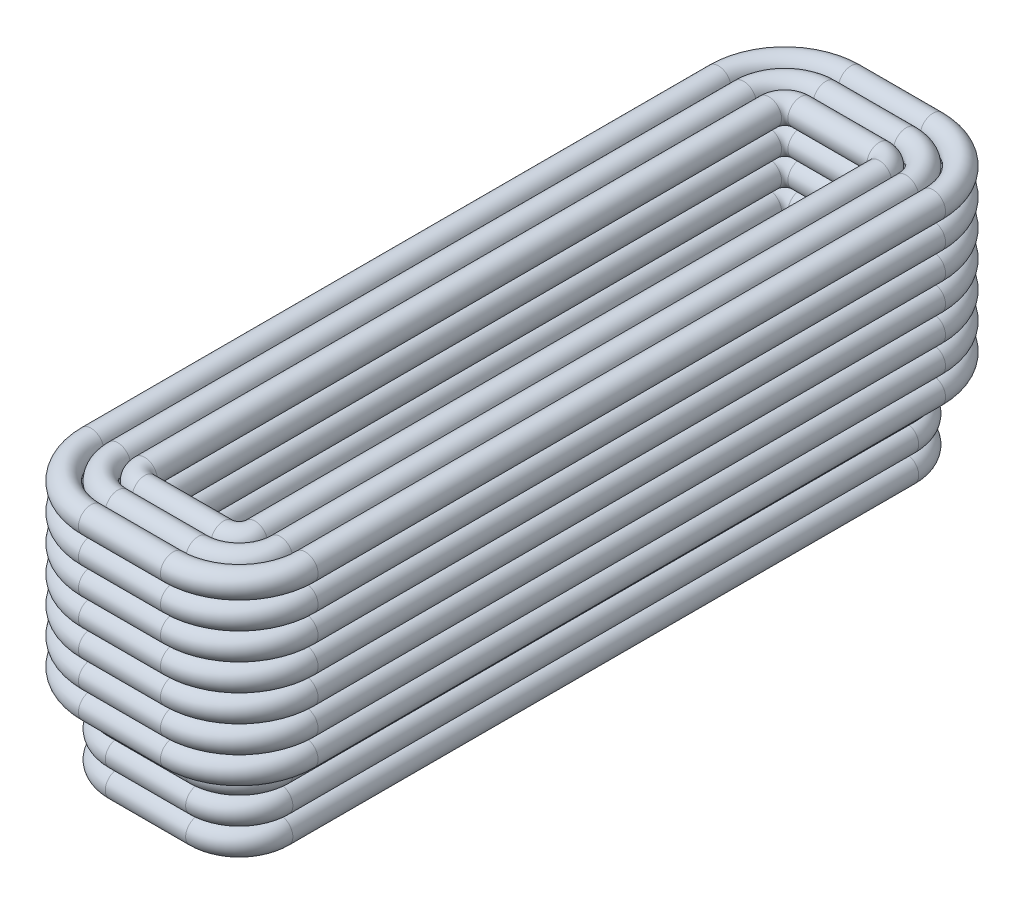
SolidWorks part; units mm, degrees
material "Copper"
ref_plane "Front Plane" through (0, 0, 0) normal (0, 0, 1) x (1, 0, 0)
ref_plane "Top Plane" through (0, 0, 0) normal (0, 1, 0) x (1, 0, 0)
ref_plane "Right Plane" through (0, 0, 0) normal (1, 0, 0) x (0, 0, -1)
ref_plane "Plane1" through (0, 41.1208, 0) normal (0, 1, 0) x (1, 0, 0)
sketch "Sketch2" plane through (0, 41.1208, 0) normal (0, 1, 0) x (1, 0, 0)
  line L1 (-1.25, -20.4) -> (1.25, -20.4)
  line L2 (-1.75, -19.9) -> (-1.75, -0.1)
  line L3 (-1.25, 0.4) -> (1.25, 0.4)
  line L4 (1.75, -19.9) -> (1.75, -0.1)
  line L5 (-1.75, -20.4) -> (1.75, 0.4) construction
  line L6 (-1.75, 0.4) -> (1.75, -20.4) construction
  line L7 (0, 0) -> (0, -10) construction
  arc A0 (-1.75, -0.1) -> (-1.25, 0.4) centre (-1.25, -0.1) cw
  arc A1 (1.25, 0.4) -> (1.75, -0.1) centre (1.25, -0.1) cw
  arc A2 (1.25, -20.4) -> (1.75, -19.9) centre (1.25, -19.9) ccw
  arc A3 (-1.25, -20.4) -> (-1.75, -19.9) centre (-1.25, -19.9) cw
  point P0 (0, -10)
  point P5 (0, -10)
  dimension "D4" = 0.5
  dimension "D1" = 10
  dimension "D2" = 20.8
  dimension "D3" = 3.5
sweep "Sweep1" add path "Sketch2" circular profile diameter 0.8 parameters "D3"=0.8
sketch "Sketch4" plane through (0, 41.1208, 0) normal (0, 1, 0) x (1, 0, 0)
  line L1 (-1.275, 1.225) -> (1.275, 1.225)
  line L2 (-2.575, -0.075) -> (-2.575, -19.925)
  line L3 (-1.275, -21.225) -> (1.275, -21.225)
  line L4 (2.575, -0.075) -> (2.575, -19.925)
  line L5 (-2.575, 1.225) -> (2.575, -21.225) construction
  line L6 (-2.575, -21.225) -> (2.575, 1.225) construction
  arc A0 (1.275, 1.225) -> (2.575, -0.075) centre (1.275, -0.075) cw
  arc A1 (-1.275, 1.225) -> (-2.575, -0.075) centre (-1.275, -0.075) ccw
  arc A2 (1.275, -21.225) -> (2.575, -19.925) centre (1.275, -19.925) ccw
  arc A3 (-2.575, -19.925) -> (-1.275, -21.225) centre (-1.275, -19.925) ccw
  point P0 (0, -10)
  point P6 (0, -10)
  dimension "D3" = 1.3
  dimension "D1" = 22.45
  dimension "D2" = 5.15
sweep "Sweep2" add path "Sketch4" circular profile diameter 0.8 parameters "D3"=0.8
pattern_linear "LPattern1" count 10 spacing 0.85 along (0, 1, 0) of "Sweep1"
ref_plane "Plane2" through (0, 48.7708, 0) normal (0, 1, 0) x (1, 0, 0)
sketch "Sketch351" plane through (0, 48.7708, 0) normal (0, 1, 0) x (1, 0, 0)
  line L1 (-1.3, -22.05) -> (1.3, -22.05)
  line L2 (-3.4, -19.95) -> (-3.4, -0.05)
  line L3 (-1.3, 2.05) -> (1.3, 2.05)
  line L4 (3.4, -19.95) -> (3.4, -0.05)
  line L5 (-3.4, -22.05) -> (3.4, 2.05) construction
  line L6 (-3.4, 2.05) -> (3.4, -22.05) construction
  arc A0 (1.3, -22.05) -> (3.4, -19.95) centre (1.3, -19.95) ccw
  arc A1 (-1.3, -22.05) -> (-3.4, -19.95) centre (-1.3, -19.95) cw
  arc A2 (-3.4, -0.05) -> (-1.3, 2.05) centre (-1.3, -0.05) cw
  arc A3 (1.3, 2.05) -> (3.4, -0.05) centre (1.3, -0.05) cw
  point P0 (0, -10)
  point P18 (0, 0)
  point P19 (0, 0)
  point P20 (1.2, -19.85)
  point P21 (1.2, -19.85)
  point P22 (1.2, -19.85)
  point P23 (0, 0)
  dimension "D3" = 2.1
  dimension "D1" = 24.1
  dimension "D2" = 6.8
sweep "Sweep3" add path "Sketch351" circular profile diameter 0.8 parameters "D3"=0.8
pattern_linear "LPattern3" count 7 spacing 0.85 along (0, -1, 0) of bodies 121
